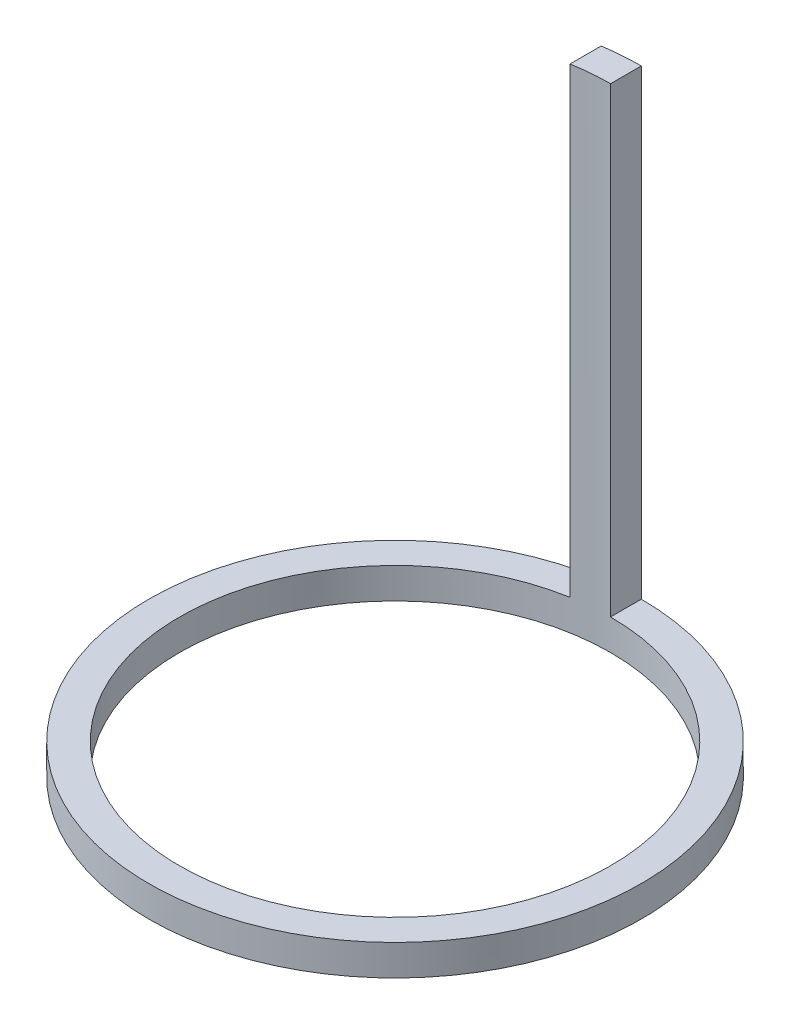
SolidWorks part; units mm, degrees
ref_plane "Front Plane" through (0, 0, 0) normal (0, 0, 1) x (1, 0, 0)
ref_plane "Top Plane" through (0, 0, 0) normal (0, 1, 0) x (1, 0, 0)
ref_plane "Right Plane" through (0, 0, 0) normal (1, 0, 0) x (0, 0, -1)
sketch "Sketch1" plane through (0, 0, 0) normal (0, 1, 0) x (1, 0, 0)
  circle A0 centre (0, 0) radius 50.8
  circle A1 centre (0, 0) radius 44.45
extrude "Boss-Extrude1" add sketch "Sketch1" along normal blind 6.35
sketch "Sketch2" plane through (0, 6.35, 0) normal (0, 1, 0) x (1, 0, 0)
  line L0 (-7.7047, 50.2123) -> (-7.7047, 43.7772)
  line L1 (0, 50.8) -> (0, 44.45)
  arc A0 (-7.7047, 50.2123) -> (0, 50.8) centre (0, 0) cw
  circle A1 centre (0, 0) radius 50.8 construction
  circle A3 centre (0, 0) radius 44.45 construction
  arc A4 (-7.7047, 43.7772) -> (0, 44.45) centre (0, 0) cw
  circle M1 centre (0, 0) radius 50.8
  circle M2 centre (0, 0) radius 44.45
extrude "Boss-Extrude2" add sketch "Sketch2" along normal blind 95.25 contours L1 L0 M1 M2
